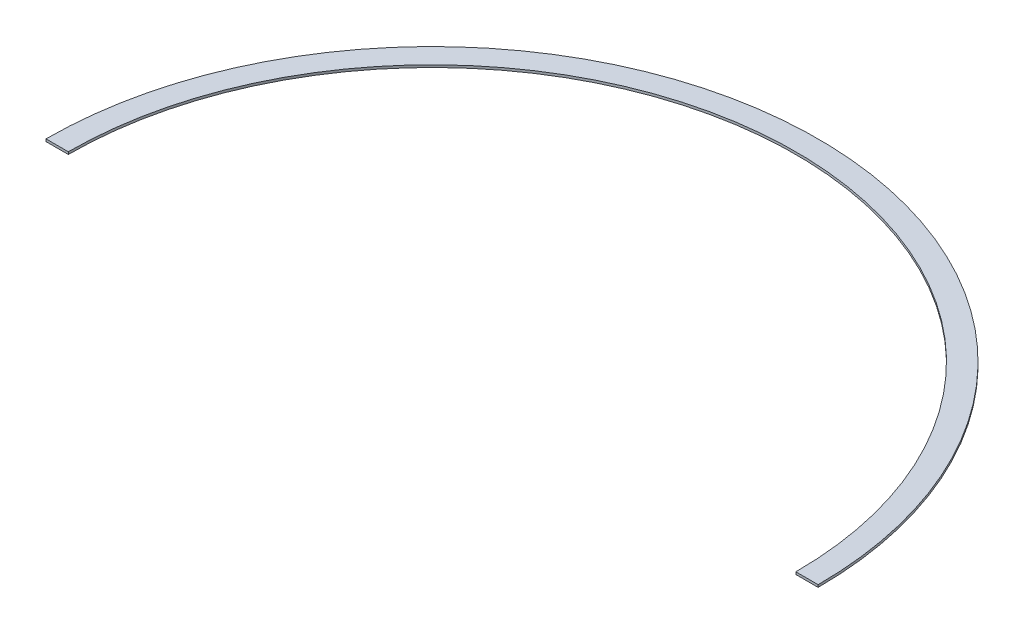
SolidWorks part; units mm, degrees
ref_plane "Front" through (0, 0, 0) normal (0, 0, 1) x (1, 0, 0)
ref_plane "Top" through (0, 0, 0) normal (0, 1, 0) x (1, 0, 0)
ref_plane "Right" through (0, 0, 0) normal (1, 0, 0) x (0, 0, -1)
sketch "Sketch1" plane through (0, 0, 0) normal (0, 1, 0) x (1, 0, 0)
  line L0 (-161.5, 0) -> (-152.17, 0)
  line L1 (152.17, 0) -> (161.5, 0)
  arc A0 (152.17, 0) -> (-152.17, 0) centre (0, 0) ccw
  arc A1 (161.5, 0) -> (-161.5, 0) centre (0, 0) ccw
  dimension "D1" = 304.34
  dimension "D2" = 323
extrude "Boss-Extrude1" add sketch "Sketch1" along normal blind 1
